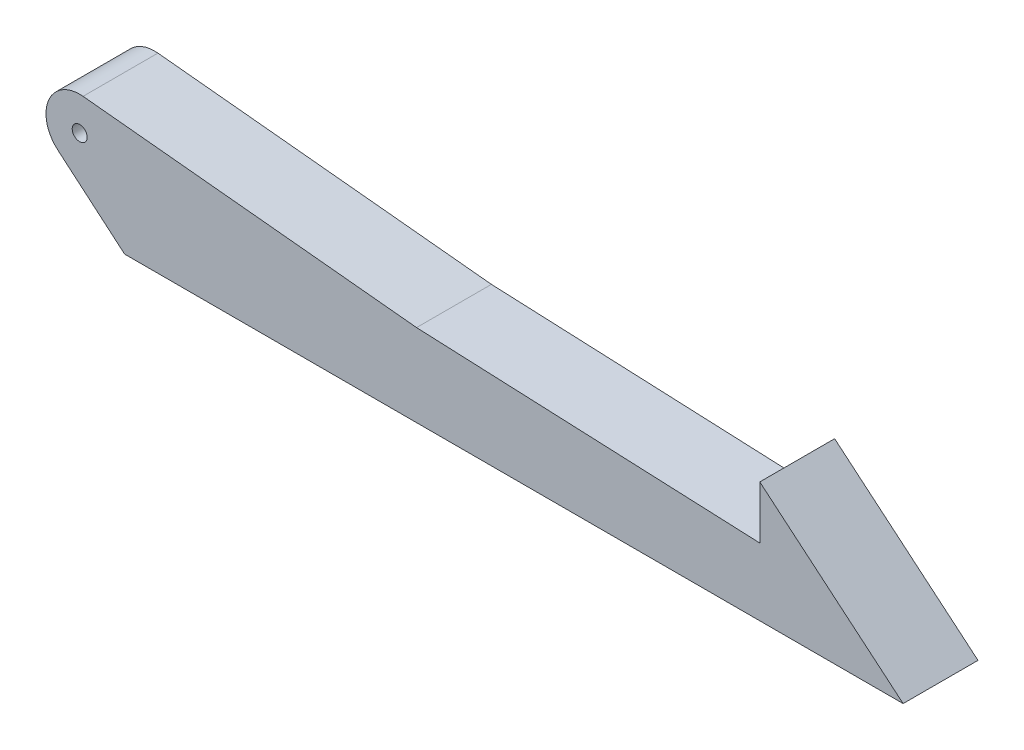
SolidWorks part; units mm, degrees
material "6061-T6 (SS)"
ref_plane "Front Plane" through (0, 0, 0) normal (0, 0, 1) x (1, 0, 0)
ref_plane "Top Plane" through (0, 0, 0) normal (0, 1, 0) x (1, 0, 0)
ref_plane "Right Plane" through (0, 0, 0) normal (1, 0, 0) x (0, 0, -1)
sketch "Sketch1" plane through (0, 0, 0) normal (0, 0, 1) x (1, 0, 0)
  line L4 (0.45, 4.4774) -> (45, 0)
  line L5 (-5, 5) -> (0, 5) construction
  line L6 (-5, 5) -> (-5, -5) construction
  line L7 (-5, -5) -> (0.0218, -5) construction
  line L10 (0, 0) -> (110, 0) construction
  line L13 (0, 0) -> (0, -11) construction
  line L14 (6, -11) -> (110, -11)
  line L15 (6, -11) -> (-2.9131, -3.4299)
  line L16 (110, -11) -> (90.8489, 5.0697)
  line L17 (45, 0) -> (90.8489, -2)
  line L18 (90.8489, 5.0697) -> (90.8489, -2)
  arc A1 (0, 5) -> (0.0218, -5) centre (0, 0) cw construction
  arc A2 (0.45, 4.4774) -> (-2.9131, -3.4299) centre (0, 0) ccw
  circle A3 centre (0, 0) radius 1
  dimension "D1" = 5
  dimension "D3" = 5
  dimension "D4" = 9
  dimension "D11" = 2
  dimension "D2" = 10
  dimension "D5" = 110
  dimension "D6" = 40
  dimension "D7" = 25
  dimension "D8" = 11
  dimension "D9" = 45
  dimension "D10" = 6
  dimension "D12" = 2
extrude "Boss-Extrude1" add sketch "Sketch1" along normal blind 10
